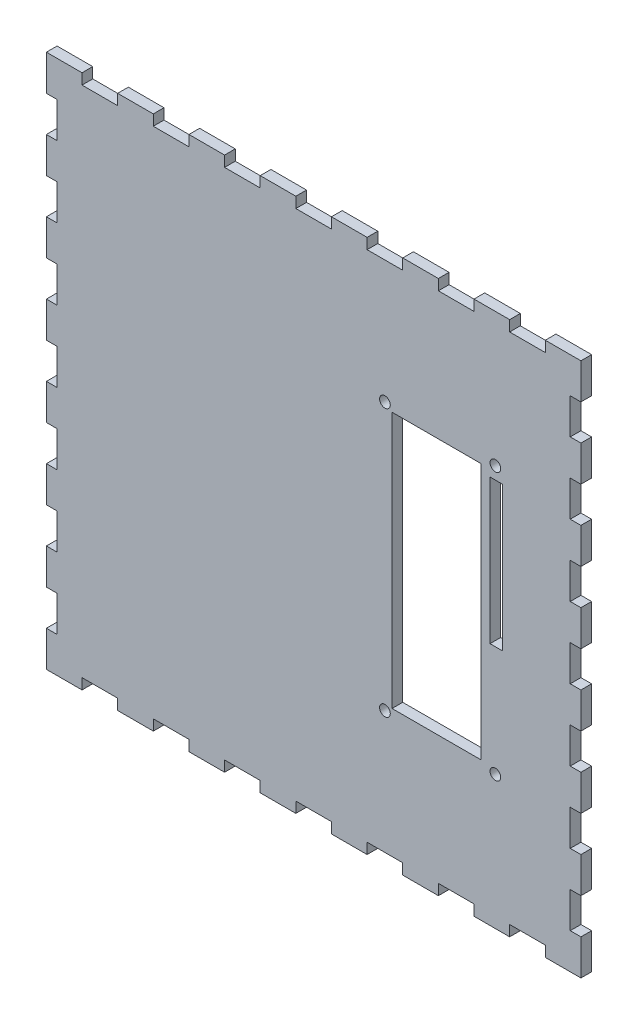
SolidWorks part; units mm, degrees
ref_plane "Alzado" through (0, 0, 0) normal (0, 0, 1) x (1, 0, 0)
ref_plane "Planta" through (0, 0, 0) normal (0, 1, 0) x (1, 0, 0)
ref_plane "Vista lateral" through (0, 0, 0) normal (1, 0, 0) x (0, 0, -1)
sketch "Croquis1" plane through (0, 0, 0) normal (0, 0, 1) x (1, 0, 0)
  line L0 (-75, -75) -> (-75, -65)
  line L1 (-75, -75) -> (-65, -75)
  line L2 (-75, 75) -> (-65, 75)
  line L3 (75, -75) -> (75, -65)
  line L4 (-75, -75) -> (75, 75) construction
  line L5 (-75, 75) -> (75, -75) construction
  line L6 (0, 0) -> (0, 48.7661) construction
  line L7 (0, 0) -> (45.0644, 0) construction
  line L10 (-65, 75) -> (-65, 72)
  line L11 (-65, 72) -> (-55, 72)
  line L12 (-55, 75) -> (-55, 72)
  line L13 (-75, 65) -> (-72, 65)
  line L15 (-75, 55) -> (-72, 55)
  line L16 (-72, 65) -> (-72, 55)
  line L17 (-45, 75) -> (-45, 72)
  line L18 (-45, 72) -> (-35, 72)
  line L19 (-35, 75) -> (-35, 72)
  line L21 (-25, 75) -> (-25, 72)
  line L22 (-25, 72) -> (-15, 72)
  line L23 (-15, 75) -> (-15, 72)
  line L25 (-5, 75) -> (-5, 72)
  line L26 (-5, 72) -> (5, 72)
  line L27 (5, 75) -> (5, 72)
  line L29 (15, 75) -> (15, 72)
  line L30 (15, 72) -> (25, 72)
  line L31 (25, 75) -> (25, 72)
  line L33 (35, 75) -> (35, 72)
  line L34 (35, 72) -> (45, 72)
  line L35 (45, 75) -> (45, 72)
  line L37 (55, 75) -> (55, 72)
  line L38 (55, 72) -> (65, 72)
  line L39 (65, 75) -> (65, 72)
  line L40 (-75, 45) -> (-72, 45)
  line L42 (-75, 35) -> (-72, 35)
  line L43 (-72, 45) -> (-72, 35)
  line L44 (-75, 25) -> (-72, 25)
  line L46 (-75, 15) -> (-72, 15)
  line L47 (-72, 25) -> (-72, 15)
  line L48 (-75, 5) -> (-72, 5)
  line L50 (-75, -5) -> (-72, -5)
  line L51 (-72, 5) -> (-72, -5)
  line L52 (-75, -15) -> (-72, -15)
  line L54 (-75, -25) -> (-72, -25)
  line L55 (-72, -15) -> (-72, -25)
  line L56 (-75, -35) -> (-72, -35)
  line L58 (-75, -45) -> (-72, -45)
  line L59 (-72, -35) -> (-72, -45)
  line L60 (-75, -55) -> (-72, -55)
  line L62 (-75, -65) -> (-72, -65)
  line L63 (-72, -55) -> (-72, -65)
  line L64 (65, -75) -> (65, -72)
  line L65 (55, -72) -> (65, -72)
  line L66 (55, -75) -> (55, -72)
  line L68 (45, -75) -> (45, -72)
  line L69 (35, -72) -> (45, -72)
  line L70 (35, -75) -> (35, -72)
  line L72 (25, -75) -> (25, -72)
  line L73 (15, -72) -> (25, -72)
  line L74 (15, -75) -> (15, -72)
  line L76 (5, -75) -> (5, -72)
  line L77 (-5, -72) -> (5, -72)
  line L78 (-5, -75) -> (-5, -72)
  line L80 (-15, -75) -> (-15, -72)
  line L81 (-25, -72) -> (-15, -72)
  line L82 (-25, -75) -> (-25, -72)
  line L84 (-35, -75) -> (-35, -72)
  line L85 (-45, -72) -> (-35, -72)
  line L86 (-45, -75) -> (-45, -72)
  line L87 (-55, -75) -> (-55, -72)
  line L88 (-65, -72) -> (-55, -72)
  line L89 (-65, -75) -> (-65, -72)
  line L92 (72, -55) -> (72, -65)
  line L93 (75, -65) -> (72, -65)
  line L95 (75, -55) -> (72, -55)
  line L96 (72, -35) -> (72, -45)
  line L97 (75, -45) -> (72, -45)
  line L99 (75, -35) -> (72, -35)
  line L100 (72, -15) -> (72, -25)
  line L101 (75, -25) -> (72, -25)
  line L103 (75, -15) -> (72, -15)
  line L104 (72, 5) -> (72, -5)
  line L105 (75, -5) -> (72, -5)
  line L107 (75, 5) -> (72, 5)
  line L108 (72, 25) -> (72, 15)
  line L109 (75, 15) -> (72, 15)
  line L111 (75, 25) -> (72, 25)
  line L112 (72, 45) -> (72, 35)
  line L113 (75, 35) -> (72, 35)
  line L115 (75, 45) -> (72, 45)
  line L116 (72, 65) -> (72, 55)
  line L117 (75, 55) -> (72, 55)
  line L119 (75, 65) -> (72, 65)
  line L125 (22, -36) -> (47, -36)
  line L126 (-55, 75) -> (-45, 75)
  line L127 (49.5, 34) -> (53, 34)
  line L128 (49.5, 34) -> (49.5, -6.5)
  line L129 (49.5, -6.5) -> (53, -6.5)
  line L130 (53, 34) -> (53, -6.5)
  line L131 (-35, 75) -> (-25, 75)
  line L132 (-15, 75) -> (-5, 75)
  line L133 (5, 75) -> (15, 75)
  line L134 (25, 75) -> (35, 75)
  line L135 (45, 75) -> (55, 75)
  line L136 (65, 75) -> (75, 75)
  line L137 (-55, -75) -> (-45, -75)
  line L138 (-35, -75) -> (-25, -75)
  line L139 (-15, -75) -> (-5, -75)
  line L140 (5, -75) -> (15, -75)
  line L141 (25, -75) -> (35, -75)
  line L142 (45, -75) -> (55, -75)
  line L143 (65, -75) -> (75, -75)
  line L144 (75, 65) -> (75, 75)
  line L145 (75, 45) -> (75, 55)
  line L146 (75, 25) -> (75, 35)
  line L147 (75, 5) -> (75, 15)
  line L148 (75, -15) -> (75, -5)
  line L149 (75, -35) -> (75, -25)
  line L150 (75, -55) -> (75, -45)
  line L151 (-75, -55) -> (-75, -45)
  line L152 (22, -36) -> (22, 36)
  line L153 (22, 36) -> (47, 36)
  line L154 (-75, -35) -> (-75, -25)
  line L155 (47, -36) -> (47, 36)
  line L156 (-75, -15) -> (-75, -5)
  line L157 (22, -36) -> (47, 36) construction
  line L158 (-75, 5) -> (-75, 15)
  line L159 (22, 36) -> (47, -36) construction
  line L160 (-75, 25) -> (-75, 35)
  line L162 (-75, 45) -> (-75, 55)
  line L163 (-75, 65) -> (-75, 75)
  circle A0 centre (20, 37.5) radius 1.5
  circle A1 centre (51, 37.5) radius 1.5
  circle A2 centre (51, -37.5) radius 1.5
  circle A3 centre (20, -37.5) radius 1.5
  point P1 (0, 0)
  point P17 (-45, 73.5)
  point P42 (-73.5, 45)
  point P134 (0, 0)
  point P135 (34.5, 0)
  point P139 (51.25, 34)
  dimension "D13" = 3
  dimension "D22" = 25
  dimension "D1" = 150
  dimension "D2" = 150
  dimension "D3" = 3
  dimension "D4" = 10
  dimension "D5" = 10
  dimension "D6" = 10
  dimension "D7" = 3
  dimension "D8" = 10
  dimension "D10" = 10
  dimension "D12" = 10
  dimension "D14" = 72
  dimension "D15" = 37.5
  dimension "D16" = 25
  dimension "D17" = 27
  dimension "D18" = 16.5
  dimension "D19" = 3.5
  dimension "D20" = 2.5
  dimension "D21" = 40.5
  dimension "D23" = 2
  dimension "D9" = 7
  dimension "D11" = 7
extrude "Saliente-Extruir1" add sketch "Croquis1" along normal blind 3
